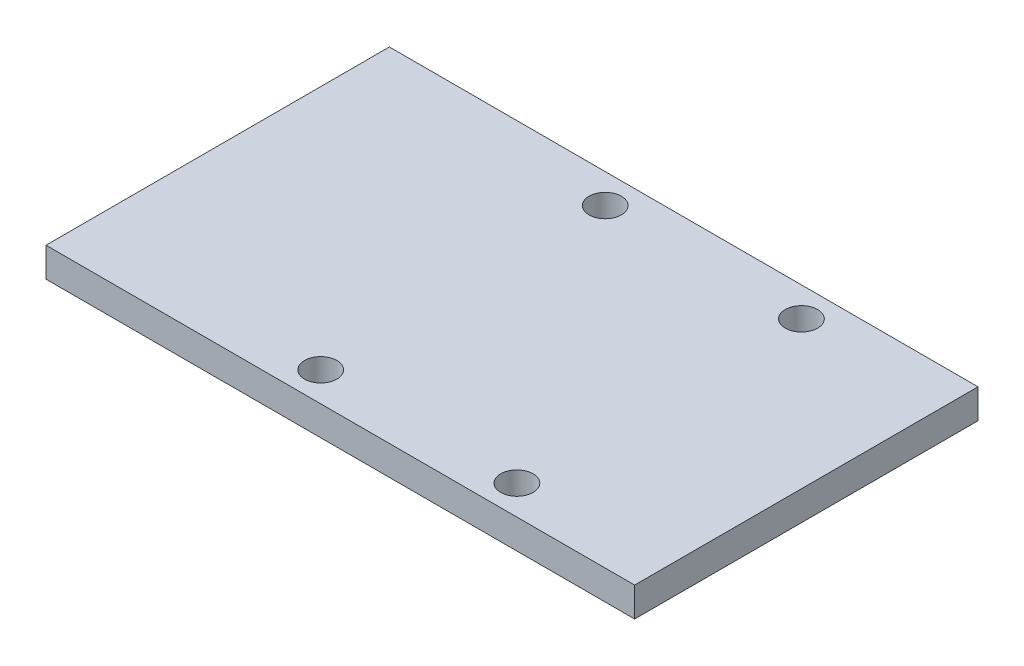
SolidWorks part; units mm, degrees
ref_plane "前视基准面" through (0, 0, 0) normal (0, 0, 1) x (1, 0, 0)
ref_plane "上视基准面" through (0, 0, 0) normal (0, 1, 0) x (1, 0, 0)
ref_plane "右视基准面" through (0, 0, 0) normal (1, 0, 0) x (0, 0, -1)
other "Configuration Table"
sketch "草图1" plane through (0, 0, 0) normal (0, 1, 0) x (1, 0, 0)
  line L1 (-30, -17.5) -> (30, -17.5)
  line L2 (-30, -17.5) -> (-30, 17.5)
  line L3 (-30, 17.5) -> (30, 17.5)
  line L4 (30, -17.5) -> (30, 17.5)
  line L5 (-30, -17.5) -> (30, 17.5) construction
  line L6 (-30, 17.5) -> (30, -17.5) construction
  point P0 (0, 0)
  dimension "D1" = 35
  dimension "D2" = 60
extrude "凸台-拉伸1" add sketch "草图1" along normal blind 3
sketch "草图2" plane through (0, 0, 0) normal (0, -1, 0) x (1, 0, 0)
  circle A0 centre (15, 14.5) radius 1.65 construction
  circle A1 centre (-5, 14.5) radius 1.65 construction
  circle A2 centre (15, 14.5) radius 1.65
  circle A3 centre (-5, 14.5) radius 1.65
  circle A4 centre (-5, -14.5) radius 1.65 construction
  circle A5 centre (15, -14.5) radius 1.65 construction
  circle A6 centre (-5, -14.5) radius 1.65
  circle A7 centre (15, -14.5) radius 1.65
extrude "切除-拉伸1" cut sketch "草图2" against normal blind 3
